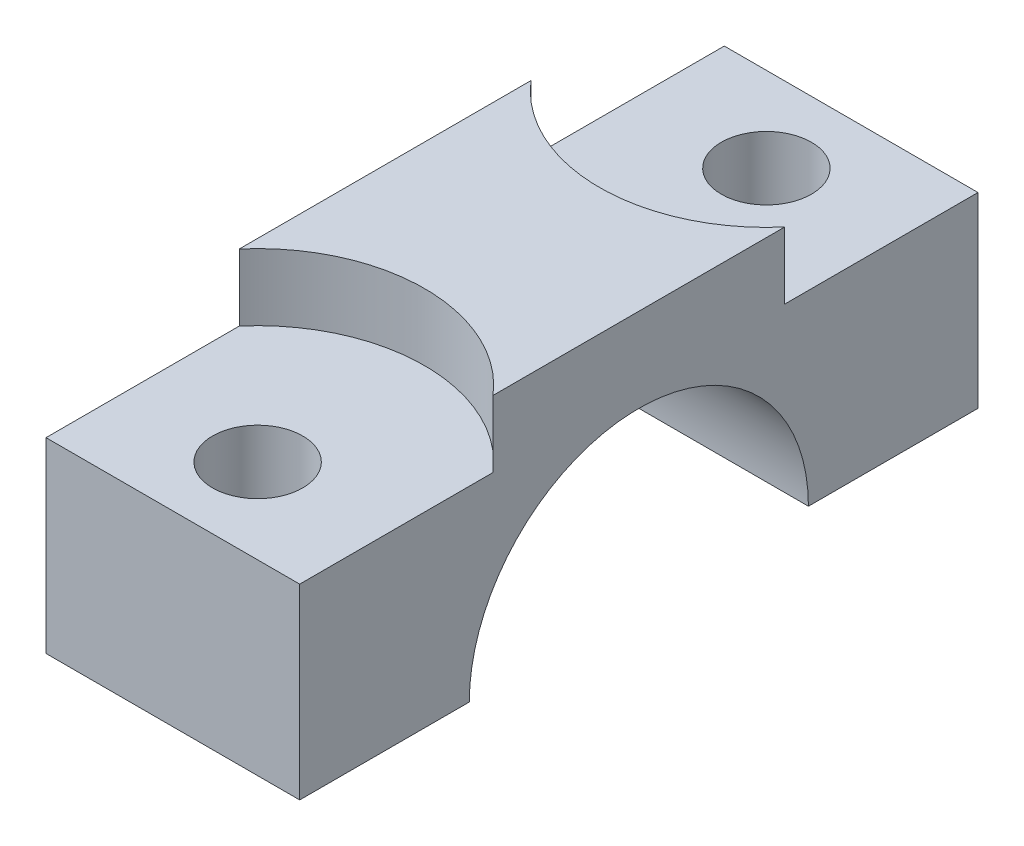
SolidWorks part; units mm, degrees
ref_plane "Front Plane" through (0, 0, 0) normal (0, 0, 1) x (1, 0, 0)
ref_plane "Top Plane" through (0, 0, 0) normal (0, 1, 0) x (1, 0, 0)
ref_plane "Right Plane" through (0, 0, 0) normal (1, 0, 0) x (0, 0, -1)
sketch "Sketch1" plane through (0, 0, 0) normal (1, 0, 0) x (0, 0, -1)
  line L1 (-25.4, 19) -> (25.4, 19)
  line L2 (-25.4, 19) -> (-25.4, 0)
  line L3 (-25.4, 0) -> (25.4, 0)
  line L4 (25.4, 19) -> (25.4, 0)
  circle A0 centre (0, 0) radius 12.7
  dimension "D3" = 25.4
  dimension "D1" = 50.8
  dimension "D2" = 19
extrude "Boss-Extrude1" add sketch "Sketch1" along normal mid plane 19 contours A0 L3 L4 L1 L2
sketch "Sketch7" plane through (0, 19, 0) normal (0, 1, 0) x (1, 0, 0)
  line L0 (0, -25.4) -> (0, -12.7) construction
  line L2 (0, 12.7) -> (0, 25.4) construction
  point P4 (0, -19.05)
  point P9 (0, 19.05)
hole_wizard "CBORE for M12 Hex Head Cap Screw3" positions "3DSketch5" profile "Sketch9" counterbore size "M12" standard "ISO" end condition through all
sketch3d "3DSketch5"
  point P0 (0, 19, -19.05)
  point P3 (0, 19, 19.05)
sketch "Sketch9" plane through (0, 19, -19.05) normal (1, 0, 0) x (0, 0, 1)
  line L0 (0, 0) -> (0, 19)
  line L1 (0, 19) -> (3.375, 19)
  line L3 (3.375, 19) -> (3.375, 5)
  line L4 (3.375, 5) -> (12.5, 5)
  line L5 (12.5, 5) -> (12.5, 0)
  line L7 (12.5, 0) -> (0, 0)
  line L11 (0, -6.35) -> (0, 107.95) construction
  dimension "Thru Hole Dia." = 6.75
  dimension "Thru Hole Depth" = 19
  dimension "C'Bore Dia." = 25
  dimension "C'Bore Depth" = 5
